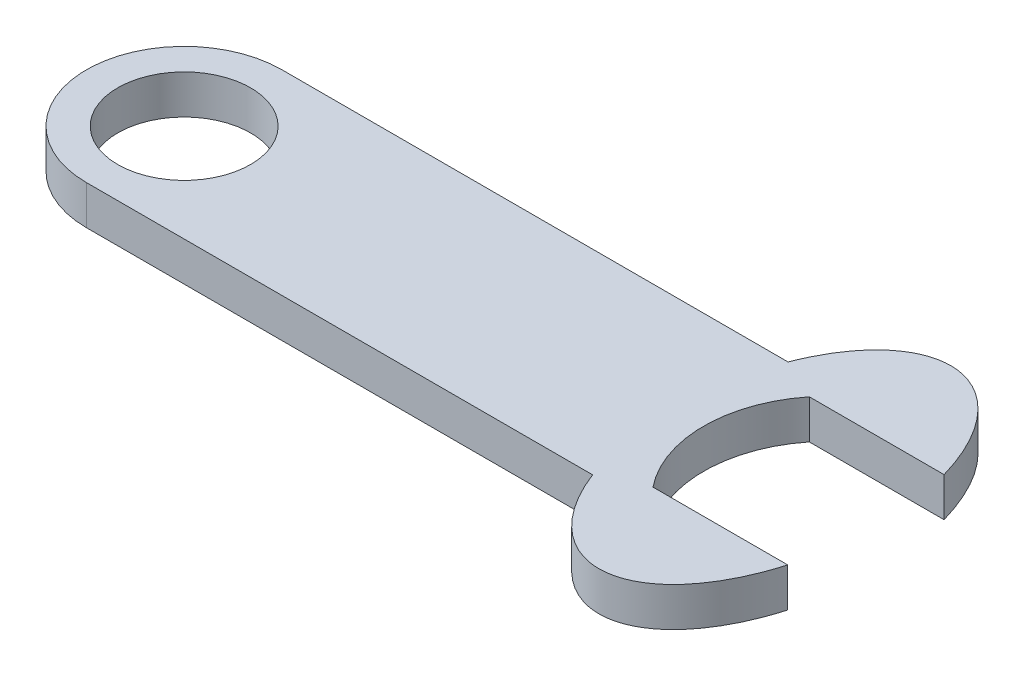
SolidWorks part; units mm, degrees
ref_plane "Front Plane" through (0, 0, 0) normal (0, 0, 1) x (1, 0, 0)
ref_plane "Top Plane" through (0, 0, 0) normal (0, 1, 0) x (1, 0, 0)
ref_plane "Right Plane" through (0, 0, 0) normal (1, 0, 0) x (0, 0, -1)
sketch "Sketch1" plane through (0, 0, 0) normal (0, 1, 0) x (1, 0, 0)
  line L0 (0, 0) -> (46333.7797, 0) construction
  line L1 (0, 0) -> (0, 46333.7797) construction
  line L2 (164.9, 0) -> (164.9, 50000) construction
  line L3 (151.1, 0) -> (151.1, 50000) construction
  line L4 (139.9201, 20) -> (174.391, 20)
  line L5 (139.9201, -20) -> (174.391, -20)
  line L6 (0, 25) -> (129.4815, 25)
  line L7 (0, -25) -> (129.4815, -25)
  line L8 (132.9, 72.3373) -> (132.9, 50072.3373) construction
  circle A0 centre (0, 0) radius 17
  arc A1 (0, 25) -> (0, -25) centre (0, 0) ccw
  arc A3 (139.9201, -20) -> (139.9201, 20) centre (164.9, 0) cw
  ellipse E0 centre (151.1, 0) end of major axis (151.1, -45) minor radius 26 (174.391, 20) -> (129.4815, 25) ccw
  ellipse E1 centre (151.1, 0) end of major axis (151.1, -45) minor radius 26 (129.4815, -25) -> (174.391, -20) ccw
  dimension "D1" = 50
  dimension "D2" = 34
  dimension "D7" = 31.9999
  dimension "D9" = 26
  dimension "D10" = 45
  dimension "D3" = 45
  dimension "D4" = 26
  dimension "D5" = 13.8
  dimension "D6" = 164.9
  dimension "D8" = 20
  dimension "D11" = 35.4185
extrude "Boss-Extrude1" add sketch "Sketch1" along normal blind 10
